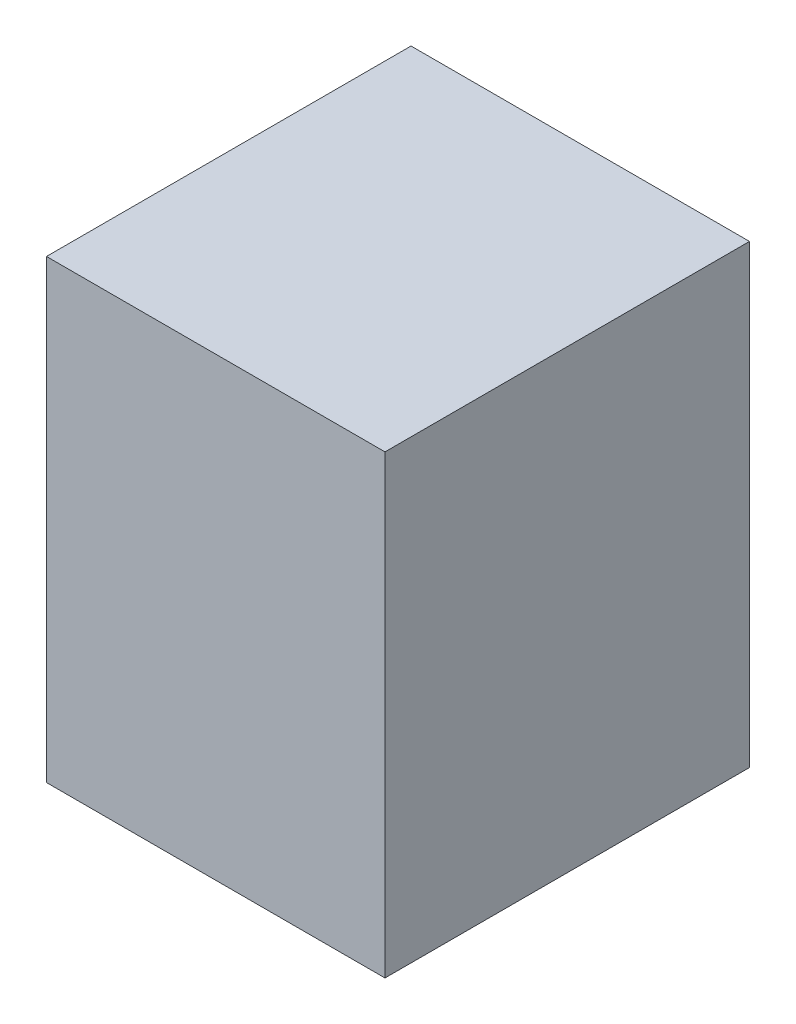
SolidWorks part; units mm, degrees
ref_plane "Front Plane" through (0, 0, 0) normal (0, 0, 1) x (1, 0, 0)
ref_plane "Top Plane" through (0, 0, 0) normal (0, 1, 0) x (1, 0, 0)
ref_plane "Right Plane" through (0, 0, 0) normal (1, 0, 0) x (0, 0, -1)
sketch "Sketch1" plane through (0, 0, 0) normal (0, 1, 0) x (1, 0, 0)
  line L1 (-165.1, 177.8) -> (165.1, 177.8)
  line L2 (-165.1, 177.8) -> (-165.1, -177.8)
  line L3 (-165.1, -177.8) -> (165.1, -177.8)
  line L4 (165.1, 177.8) -> (165.1, -177.8)
  line L5 (-165.1, 177.8) -> (165.1, -177.8) construction
  line L6 (-165.1, -177.8) -> (165.1, 177.8) construction
  point P0 (0, 0)
  dimension "D1" = 330.2
  dimension "D2" = 355.6
extrude "Boss-Extrude1" add sketch "Sketch1" along normal blind 444.5
